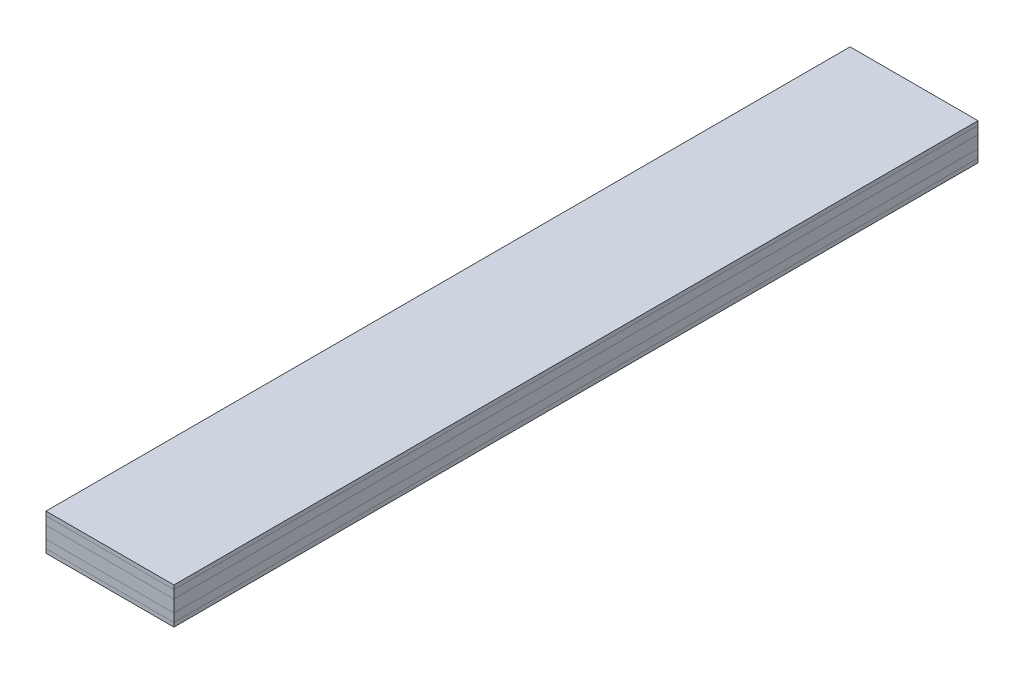
SolidWorks part; units mm, degrees
ref_plane "Front Plane" through (0, 0, 0) normal (0, 0, 1) x (1, 0, 0)
ref_plane "Top Plane" through (0, 0, 0) normal (0, 1, 0) x (1, 0, 0)
ref_plane "Right Plane" through (0, 0, 0) normal (1, 0, 0) x (0, 0, -1)
sketch "Sketch1" plane through (0, 0, 0) normal (0, 1, 0) x (1, 0, 0)
  line L0 (-304.8, 609.6) -> (304.8, 609.6) construction
  line L1 (304.8, 609.6) -> (304.8, -609.6) construction
  line L2 (0, 609.6) -> (0, 0) construction
  line L3 (0, 0) -> (304.8, 0) construction
  dimension "Width" = 609.6
  dimension "Length" = 1219.2
sketch "Sketch2" plane through (0, 0, 0) normal (1, 0, 0) x (0, 0, -1)
  line L0 (609.6, 0) -> (609.6, -25.4) construction
  dimension "Thickness" = 25.4
sketch "Sketch3" plane through (0, 0, 0) normal (0, 1, 0) x (1, 0, 0)
  line L1 (-304.8, 609.6) -> (304.8, 609.6)
  line L2 (-304.8, 609.6) -> (-304.8, -609.6)
  line L3 (-304.8, -609.6) -> (304.8, -609.6)
  line L4 (304.8, 609.6) -> (304.8, -609.6)
extrude "Boss-Extrude1" add sketch "Sketch3" against normal up to vertex (25.4 mm away) up to point (0, -25.4, -609.6)
sketch "Sketch4" plane through (0, 0, 0) normal (0, 0, 1) x (1, 0, 0)
  line L0 (0, -11.2889) -> (0, -14.1111) construction
  line L1 (-335.28, -22.5778) -> (335.28, -22.5778)
  line L2 (0, 0) -> (0, -25.4) construction
  line L3 (0, -11.2889) -> (0, -8.4667) construction
  line L4 (0, -14.1111) -> (0, -16.9333) construction
  line L5 (0, -8.4667) -> (0, -5.6444) construction
  line L6 (0, -5.6444) -> (0, -2.8222) construction
  line L7 (0, -2.8222) -> (0, 0) construction
  line L8 (0, -16.9333) -> (0, -19.7556) construction
  line L9 (0, -19.7556) -> (0, -22.5778) construction
  line L10 (0, -22.5778) -> (0, -25.4) construction
  line L11 (-335.28, -16.9333) -> (335.28, -16.9333)
  line L12 (-335.28, -2.8222) -> (335.28, -2.8222)
  line L13 (-335.28, -8.4667) -> (335.28, -8.4667)
  point P5 (0, -12.7)
  point P16 (0, -22.5778)
  point P19 (0, -16.9333)
  point P23 (0, -2.8222)
  point P25 (0, -8.4667)
  dimension "D1" = 670.56
split "Split1" trim tools "Sketch4" bodies to split 104 resulting bodies 105 106 107 108 109
sketch "Sketch6" plane through (0, 0, 0) normal (0, 1, 0) x (1, 0, 0)
  line L1 (-304.8, -609.6) -> (304.8, -609.6) construction
  line L2 (215.9, -609.6) -> (215.9, -50.8)
  line L3 (215.9, -50.8) -> (304.8, -50.8)
  line L6 (-304.8, 609.6) -> (-304.8, -609.6)
  line L7 (-304.8, -609.6) -> (304.8, -609.6)
  line L8 (304.8, -609.6) -> (304.8, 609.6)
  line L9 (304.8, 609.6) -> (-304.8, 609.6)
  line M9 (-304.8, 609.6) -> (-304.8, -609.6)
  line M10 (-304.8, -609.6) -> (304.8, -609.6)
  line M11 (304.8, -609.6) -> (304.8, 609.6)
  line M12 (304.8, 609.6) -> (-304.8, 609.6)
  dimension "D1" = 558.8
extrude "Cut-Extrude1" cut sketch "Sketch6" against normal blind 25.4 contours L2 L3 M11 M12 M9 M10
equation "\"D1@Sketch4\"=\"Width@Sketch1\"*1.1"
